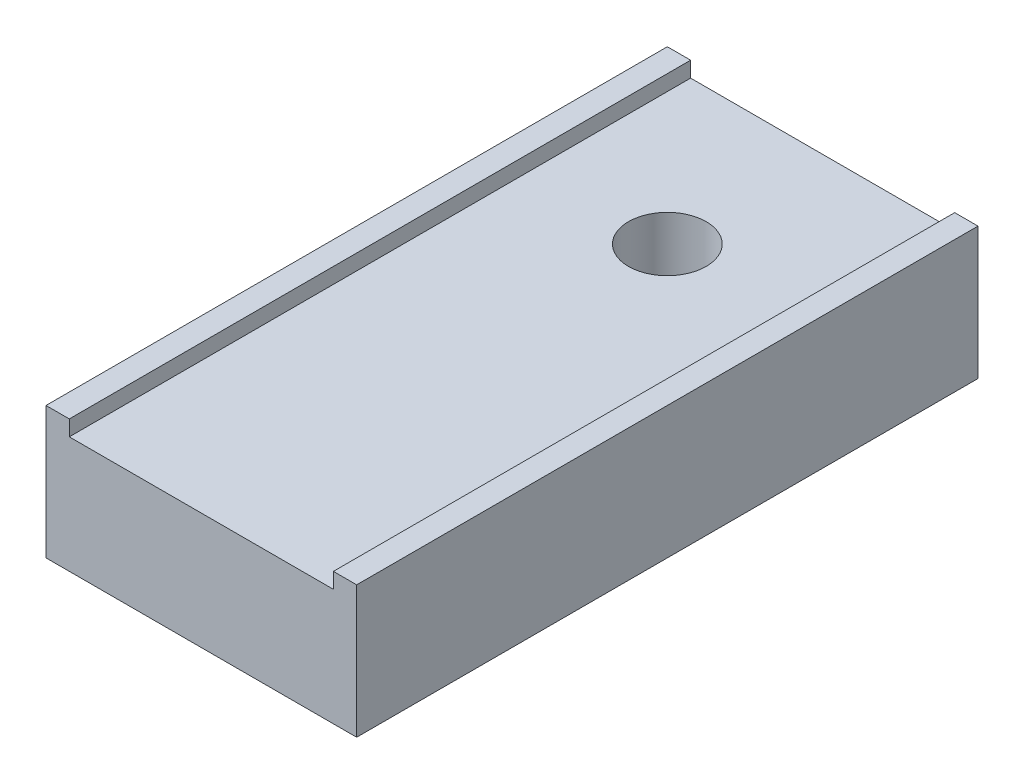
SolidWorks part; units mm, degrees
ref_plane "Front Plane" through (0, 0, 0) normal (0, 0, 1) x (1, 0, 0)
ref_plane "Top Plane" through (0, 0, 0) normal (0, 1, 0) x (1, 0, 0)
ref_plane "Right Plane" through (0, 0, 0) normal (1, 0, 0) x (0, 0, -1)
sketch "Sketch1" plane through (0, 0, 0) normal (0, 1, 0) x (1, 0, 0)
  line L1 (-12.7, -25.4) -> (12.7, -25.4)
  line L2 (-12.7, -25.4) -> (-12.7, 25.4)
  line L3 (-12.7, 25.4) -> (12.7, 25.4)
  line L4 (12.7, -25.4) -> (12.7, 25.4)
  line L5 (-12.7, -25.4) -> (12.7, 25.4) construction
  line L6 (-12.7, 25.4) -> (12.7, -25.4) construction
  point P0 (0, 0)
  dimension "D1" = 25.4
  dimension "D2" = 50.8
extrude "Boss-Extrude1" add sketch "Sketch1" along normal blind 9.525
sketch "Sketch2" plane through (0, 9.525, 0) normal (0, 1, 0) x (1, 0, 0)
  line L0 (-12.7, -25.4) -> (12.7, -25.4) construction
  line L1 (-12.7, 25.4) -> (-10.795, 25.4)
  line L2 (-12.7, 25.4) -> (-12.7, -25.4)
  line L3 (-12.7, -25.4) -> (-10.795, -25.4)
  line L4 (-10.795, 25.4) -> (-10.795, -25.4)
  line L5 (-10.795, 0) -> (10.795, 0) construction
  line L6 (12.7, 25.4) -> (10.795, 25.4)
  line L7 (12.7, 25.4) -> (12.7, -25.4)
  line L8 (12.7, -25.4) -> (10.795, -25.4)
  line L9 (10.795, 25.4) -> (10.795, -25.4)
  dimension "D1" = 21.59
extrude "Boss-Extrude2" add sketch "Sketch2" along normal blind 1.27
sketch "Sketch3" plane through (0, 9.525, 0) normal (0, 1, 0) x (1, 0, 0)
  line L0 (10.795, 25.4) -> (-10.795, 25.4) construction
  circle A0 centre (0, 12.7) radius 3.175
  point P2 (0, 0)
  dimension "D1" = 6.35
  dimension "D2" = 12.7
extrude "Cut-Extrude1" cut sketch "Sketch3" against normal through all both and the other way through all
